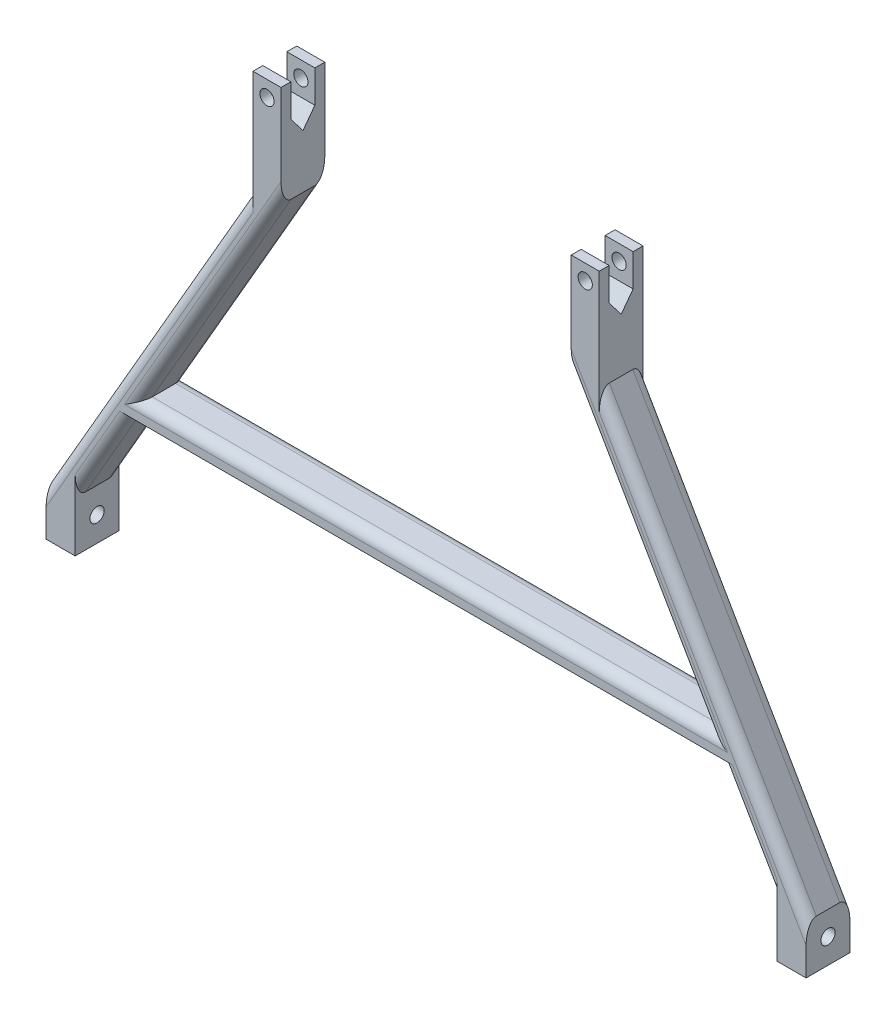
SolidWorks part; units mm, degrees
ref_plane "Front Plane" through (0, 0, 0) normal (0, 0, 1) x (1, 0, 0)
ref_plane "Top Plane" through (0, 0, 0) normal (0, 1, 0) x (1, 0, 0)
ref_plane "Right Plane" through (0, 0, 0) normal (1, 0, 0) x (0, 0, -1)
sketch "Sketch1" plane through (0, 0, 0) normal (0, 0, 1) x (1, 0, 0)
  line L0 (0, 0) -> (-6.985, 0)
  line L1 (-6.985, 0) -> (-6.985, -25.4119)
  line L2 (0, 0) -> (0, -25.4119)
  line L3 (0, -25.4119) -> (51.5954, -114.7777)
  line L4 (-6.985, -25.4119) -> (27.6753, -85.4453)
  line L10 (27.6753, -85.4453) -> (-6.985, -85.4453)
  line L12 (-6.985, -85.4453) -> (-79.375, -85.4453)
  line L15 (34.9037, -97.9653) -> (44.3539, -114.3334)
  line L16 (-6.985, 0) -> (-6.985, -25.4119)
  line L17 (44.3539, -114.3334) -> (44.3539, -126.8761)
  line L18 (-114.0353, -85.4453) -> (-79.375, -85.4453)
  line L19 (44.3539, -126.8761) -> (51.5954, -126.8761)
  line L20 (51.5954, -126.8761) -> (51.5954, -114.7777)
  line L21 (-43.18, -85.4453) -> (-43.18, -90.0213)
  line L24 (-137.9554, -126.8761) -> (-137.9554, -114.7777)
  line L25 (-130.7139, -126.8761) -> (-137.9554, -126.8761)
  line L26 (-130.7139, -114.3334) -> (-130.7139, -126.8761)
  line L27 (-121.2637, -97.9653) -> (-130.7139, -114.3334)
  line L28 (-86.36, -25.4119) -> (-137.9554, -114.7777)
  line L29 (-79.375, -25.4119) -> (-114.0353, -85.4453)
  line L30 (-86.36, 0) -> (-79.375, 0)
  line L31 (-86.36, 0) -> (-86.36, -25.4119)
  line L32 (-79.375, 0) -> (-79.375, -25.4119)
  line L33 (-121.2637, -97.9653) -> (-116.6773, -90.0213)
  line L34 (34.9037, -97.9653) -> (30.3173, -90.0213)
  line L35 (-116.6773, -90.0213) -> (30.3173, -90.0213)
  dimension "D1" = 6.985
  dimension "D2" = 36.195
extrude "Boss-Extrude1" add sketch "Sketch1" along normal blind 10.922
ref_plane "Plane1" through (0, 0, 0) normal (1, 0, 0) x (0, 0, -1)
sketch "Sketch3" plane through (0, 0, 0) normal (1, 0, 0) x (0, 0, -1)
  line L1 (-10.922, 0) -> (0, 0) construction
  line L2 (-2.4718, 0) -> (-2.4927, 0)
  line L3 (-8.4502, 0) -> (-8.4502, -8.0614)
  line L4 (-8.4502, -8.0614) -> (-5.461, -12.0792)
  line L6 (-2.4718, -8.0614) -> (-5.461, -12.0792)
  line L7 (-2.4718, 0) -> (-2.4718, -8.0614)
  line L8 (-8.4502, 0) -> (-2.4927, 0)
extrude "Cut-Extrude1" cut sketch "Sketch3" against normal blind 114.427
ref_plane "Plane2" through (0, 0, 10.922) normal (0, 0, 1) x (1, 0, 0)
sketch "Sketch4" plane through (0, 0, 10.922) normal (0, 0, 1) x (1, 0, 0)
  line L0 (-3.4925, 0) -> (-3.4925, -3.832)
  line L1 (0, 0) -> (-6.985, 0) construction
  circle A0 centre (-3.4925, -3.832) radius 1.778
  dimension "D1" = 3.556
extrude "Cut-Extrude2" cut sketch "Sketch4" against normal blind 114.427
sketch "Sketch5" plane through (0, 0, 10.922) normal (0, 0, 1) x (1, 0, 0)
  line L0 (-82.8675, 0) -> (-82.8675, -3.919)
  line L1 (-86.36, 0) -> (-79.375, 0) construction
  circle A0 centre (-82.8675, -3.919) radius 1.778
  dimension "D1" = 3.556
extrude "Cut-Extrude3" cut sketch "Sketch5" against normal blind 114.427
ref_plane "Plane3" through (51.5954, 0, 0) normal (1, 0, 0) x (0, 0, -1)
sketch "Sketch6" plane through (51.5954, 0, 0) normal (1, 0, 0) x (0, 0, -1)
  line L0 (-5.461, -126.8761) -> (-5.461, -120.6878)
  line L1 (-10.922, -126.8761) -> (0, -126.8761) construction
  circle A0 centre (-5.461, -120.6878) radius 1.778
  dimension "D1" = 3.556
extrude "Cut-Extrude4" cut sketch "Sketch6" against normal blind 251.079
fillet "Fillet1" radius 2.54 3 edges at (37.3356, -102.1774, 10.922) (10.3452, -55.4286, 10.922) (25.7977, -70.0948, 10.922)
fillet "Fillet2" radius 2.54 3 edges at (37.3356, -102.1774, 0) (25.7977, -70.0948, 0) (10.3452, -55.4286, 0)
fillet "Fillet3" radius 2.54 1 edges at (-41.7135, -85.4453, 10.922)
fillet "Fillet4" radius 2.54 1 edges at (-41.7135, -85.4453, 0)
fillet "Fillet5" radius 2.54 4 edges at (-97.4384, -56.6986, 0) (-123.6956, -102.1774, 10.922) (-112.1577, -70.0948, 10.922) (-97.4384, -56.6986, 10.922)
fillet "Fillet6" radius 2.54 2 edges at (-123.6956, -102.1774, 0) (-112.1577, -70.0948, 0)
